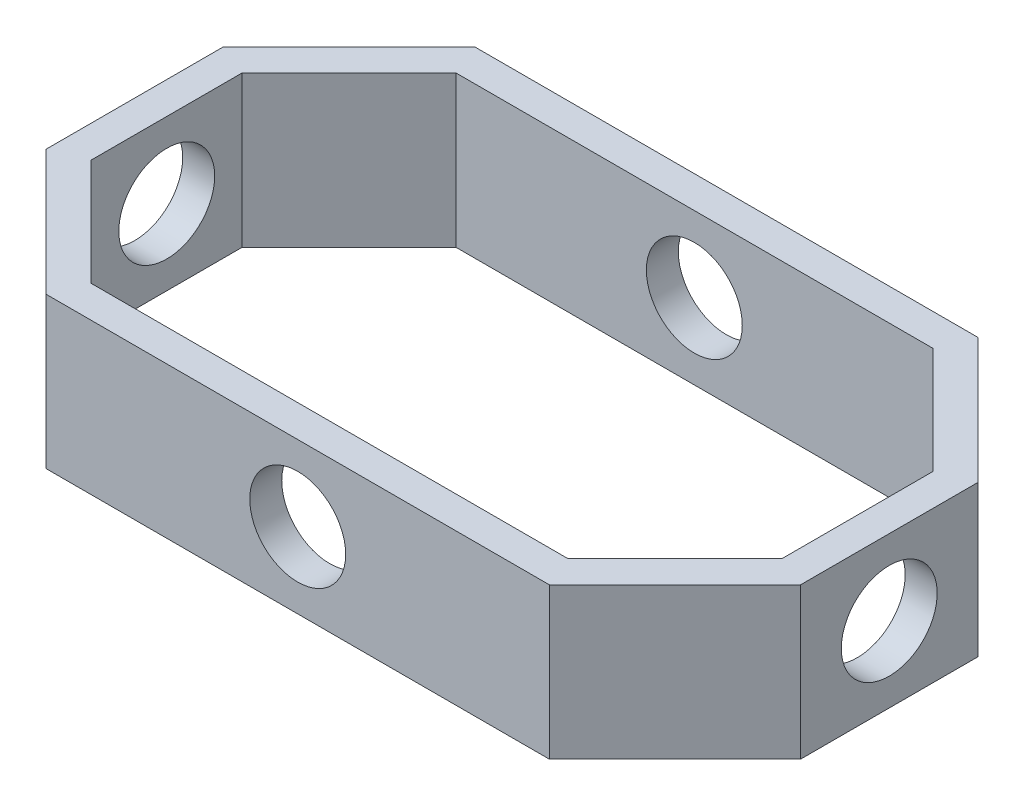
SolidWorks part; units mm, degrees
material "ABS"
ref_plane "Front Plane" through (0, 0, 0) normal (0, 0, 1) x (1, 0, 0)
ref_plane "Top Plane" through (0, 0, 0) normal (0, 1, 0) x (1, 0, 0)
ref_plane "Right Plane" through (0, 0, 0) normal (1, 0, 0) x (0, 0, -1)
sketch "Sketch3" plane through (0, 0, 0) normal (0, 1, 0) x (1, 0, 0)
  line L0 (-16.1849, 0) -> (16.1849, 0) construction
  line L17 (-25, -21.2816) -> (25, -21.2816)
  line L18 (5.0967, 8.8151) -> (-7.3697, 21.2816) construction
  line L19 (-7.3697, 21.2816) -> (-25, 21.2816) construction
  line L20 (-25, 21.2816) -> (-37.4665, 8.8151) construction
  line L21 (-37.4665, 8.8151) -> (-37.4665, -8.8151) construction
  line L22 (-37.4665, -8.8151) -> (-25, -21.2816) construction
  line L23 (-25, -21.2816) -> (-7.3697, -21.2816) construction
  line L24 (-7.3697, -21.2816) -> (5.0967, -8.8151) construction
  line L25 (5.0967, -8.8151) -> (5.0967, 8.8151) construction
  line L26 (-5.0967, 8.8151) -> (-5.0967, -8.8151) construction
  line L27 (-5.0967, -8.8151) -> (7.3697, -21.2816) construction
  line L28 (7.3697, -21.2816) -> (25, -21.2816) construction
  line L29 (25, -21.2816) -> (37.4665, -8.8151) construction
  line L30 (37.4665, -8.8151) -> (37.4665, 8.8151) construction
  line L31 (37.4665, 8.8151) -> (25, 21.2816) construction
  line L32 (25, 21.2816) -> (7.3697, 21.2816) construction
  line L33 (7.3697, 21.2816) -> (-5.0967, 8.8151) construction
  line L34 (25, -21.2816) -> (37.4665, -8.8151)
  line L35 (37.4665, -8.8151) -> (37.4665, 8.8151)
  line L36 (37.4665, 8.8151) -> (25, 21.2816)
  line L37 (25, 21.2816) -> (-25, 21.2816)
  line L38 (-25, 21.2816) -> (-37.4665, 8.8151)
  line L39 (-37.4665, 8.8151) -> (-37.4665, -8.8151)
  line L40 (-37.4665, -8.8151) -> (-25, -21.2816)
  line L41 (-34.2915, -7.5) -> (-23.6849, -18.1066)
  line L42 (-23.6849, -18.1066) -> (23.6849, -18.1066)
  line L43 (23.6849, -18.1066) -> (34.2915, -7.5)
  line L44 (34.2915, -7.5) -> (34.2915, 7.5)
  line L45 (34.2915, 7.5) -> (23.6849, 18.1066)
  line L46 (23.6849, 18.1066) -> (-23.6849, 18.1066)
  line L47 (-23.6849, 18.1066) -> (-34.2915, 7.5)
  line L48 (-34.2915, 7.5) -> (-34.2915, -7.5)
  circle A0 centre (-16.1849, 0) radius 21.2816 construction
  circle A1 centre (16.1849, 0) radius 21.2816 construction
  point P3 (0, 0)
  dimension "D1" = 15
  dimension "D2" = 50
  dimension "D3" = 3.175
ref_axis "Axis1" through (0, 0, 0) along (0, 1, 0)
extrude "Boss-Extrude2" add sketch "Sketch3" along normal blind 15
sketch "Sketch4" plane through (0, 0, 21.2816) normal (0, 0, 1) x (1, 0, 0)
  line L0 (-25, 15) -> (-25, 0) construction
  circle A0 centre (0, 7.5) radius 4.7625
  point P6 (-25, 7.5)
  dimension "D1" = 9.525
extrude "Cut-Extrude2" cut sketch "Sketch4" against normal up to next
pattern_circular "CirPattern2" count 4 over 360 about axis through (0, 0, 0) along (0, 1, 0) of "Cut-Extrude2"
